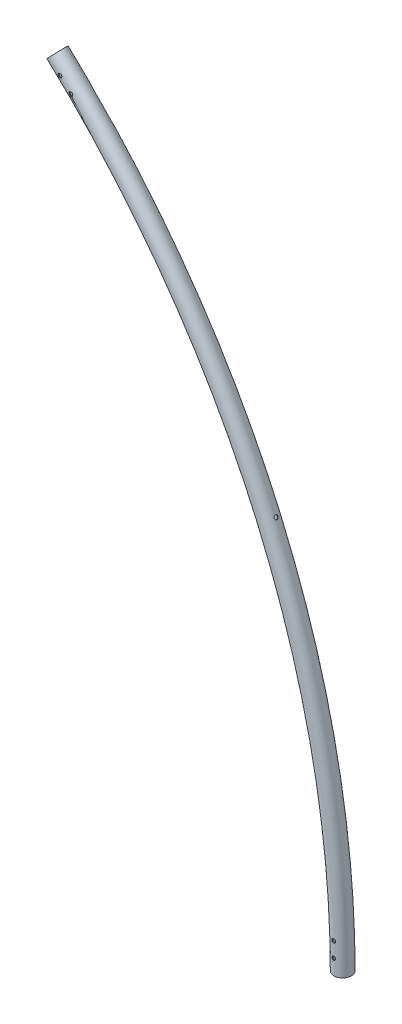
SolidWorks part; units mm, degrees
material "Galvanized Steel"
ref_plane "Front Plane" through (0, 0, 0) normal (0, 0, 1) x (1, 0, 0)
ref_plane "Top Plane" through (0, 0, 0) normal (0, 1, 0) x (1, 0, 0)
ref_plane "Right Plane" through (0, 0, 0) normal (1, 0, 0) x (0, 0, -1)
sketch "Sketch2" plane through (0, 0, 0) normal (0, 0, 1) x (1, 0, 0)
  line L2 (1384.9795, 604.8633) -> (0, 0) construction
  line L3 (0, 0) -> (1898.9305, 0) construction
  arc A0 (1027.1346, 1108.6128) -> (1511.3, 0) centre (0, 0) cw
  point P7 (1496.568, 0)
  dimension "D1" = 1511.3
  dimension "D2" = 1244.6
  dimension "D3" = 14.732
sketch "Sketch4" plane through (0, 0, 0) normal (0, 1, 0) x (1, 0, 0)
  circle A0 centre (1496.568, 0) radius 14.732
  circle A1 centre (1496.568, 0) radius 13.3223
sweep "Sweep3" add profiles "Sketch4" path "Sketch2"
sketch "Sketch8" plane through (0, 0, 0) normal (0, -1, 0) x (1, 0, 0)
  point P0 (1496.568, 0)
sketch "Sketch9" plane through (0, 0, 0) normal (-0.7335, 0.6796, 0) x (0.6796, 0.7335, 0)
  point P0 (1496.568, 0)
sketch "Sketch10" plane through (0, 0, 0) normal (0, 0, 1) x (1, 0, 0)
  arc A0 (1511.3, 0) -> (1027.1346, 1108.6128) centre (0, 0) ccw construction
  point P0 (1384.9795, 604.8633)
ref_plane "Plane2" through (1384.9795, 604.8633, 0) normal (0.9164, 0.4002, 0) x (0, 0, -1)
sketch "Sketch11" plane through (1384.9795, 604.8633, 0) normal (0.9164, 0.4002, 0) x (0, 0, -1)
  circle A0 centre (0, 0) radius 3.175
extrude "Cut-Extrude1" cut sketch "Sketch11" against normal blind 41.91
sketch "Sketch12" plane through (0, 0, 0) normal (0, 0, 1) x (1, 0, 0)
  line L0 (1027.1346, 1108.6128) -> (1007.1098, 1086.9995) construction
  line L1 (1481.836, 0) -> (1511.3, 0) construction
  circle A0 centre (1035.6547, 1080.4358) radius 3.175
  circle A1 centre (1054.0175, 1062.8824) radius 3.175
  circle A2 centre (1495.9379, 25.4) radius 3.175
  circle A3 centre (1495.9379, 50.8) radius 3.175
  dimension "D1" = 25.4
  dimension "D3" = 25.4
  dimension "D4" = 50.8
  dimension "D2" = 50.8
extrude "Cut-Extrude2" cut sketch "Sketch12" against normal through all and the other way through all
